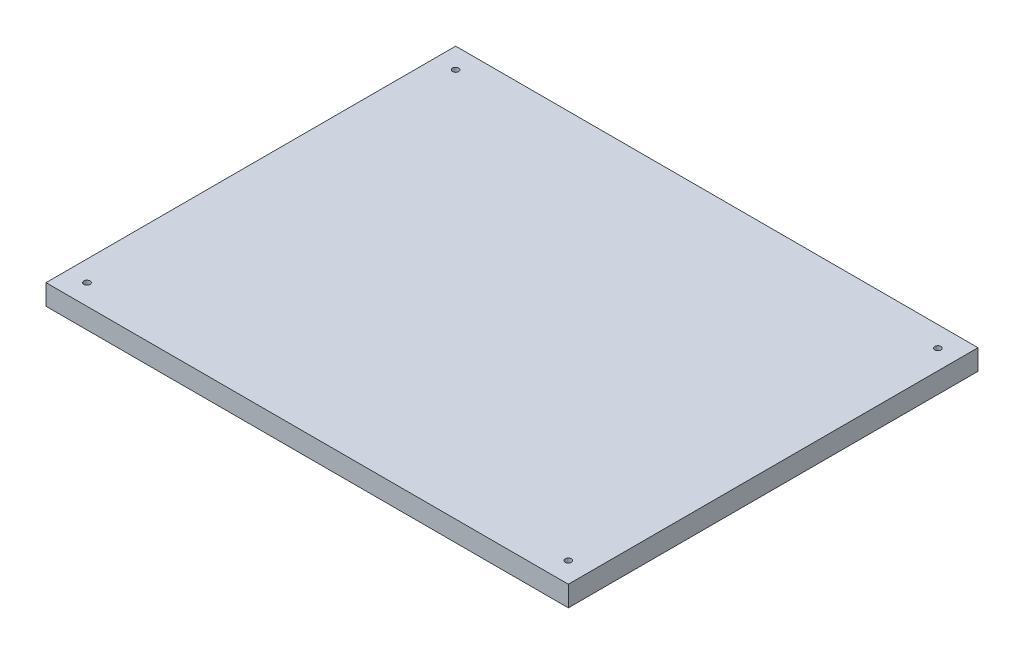
SolidWorks part; units mm, degrees
material "ABS"
ref_plane "Plano frontal" through (0, 0, 0) normal (0, 0, 1) x (1, 0, 0)
ref_plane "Plano superior" through (0, 0, 0) normal (0, 1, 0) x (1, 0, 0)
ref_plane "Plano direito" through (0, 0, 0) normal (1, 0, 0) x (0, 0, -1)
sketch "Esboço1" plane through (0, 0, 0) normal (0, 1, 0) x (1, 0, 0)
  line L1 (-127.5, -100) -> (127.5, -100)
  line L2 (-127.5, -100) -> (-127.5, 100)
  line L3 (-127.5, 100) -> (127.5, 100)
  line L4 (127.5, -100) -> (127.5, 100)
  line L5 (-127.5, -100) -> (127.5, 100) construction
  line L6 (-127.5, 100) -> (127.5, -100) construction
  point P0 (0, 0)
  dimension "D1" = 255
  dimension "D2" = 200
extrude "Ressalto-extrusão1" add sketch "Esboço1" along normal blind 10
sketch "Sketch1" plane through (0, 0, 0) normal (0, 1, 0) x (1, 0, 0)
  circle A0 centre (-117.5, 90) radius 1.5
  circle A1 centre (117.9043, 90) radius 1.5
  circle A2 centre (117.5, -90) radius 1.5
  circle A3 centre (-117.5, -90) radius 1.5
  dimension "D8" = 3
  dimension "D9" = 3
  dimension "D10" = 3
  dimension "D11" = 3
  dimension "D1" = 10
  dimension "D2" = 10
  dimension "D3" = 10
  dimension "D4" = 10
  dimension "D5" = 10
  dimension "D6" = 10
  dimension "D7" = 10
extrude "Cut-Extrude2" cut sketch "Sketch1" against normal blind 10 and the other way blind 26
